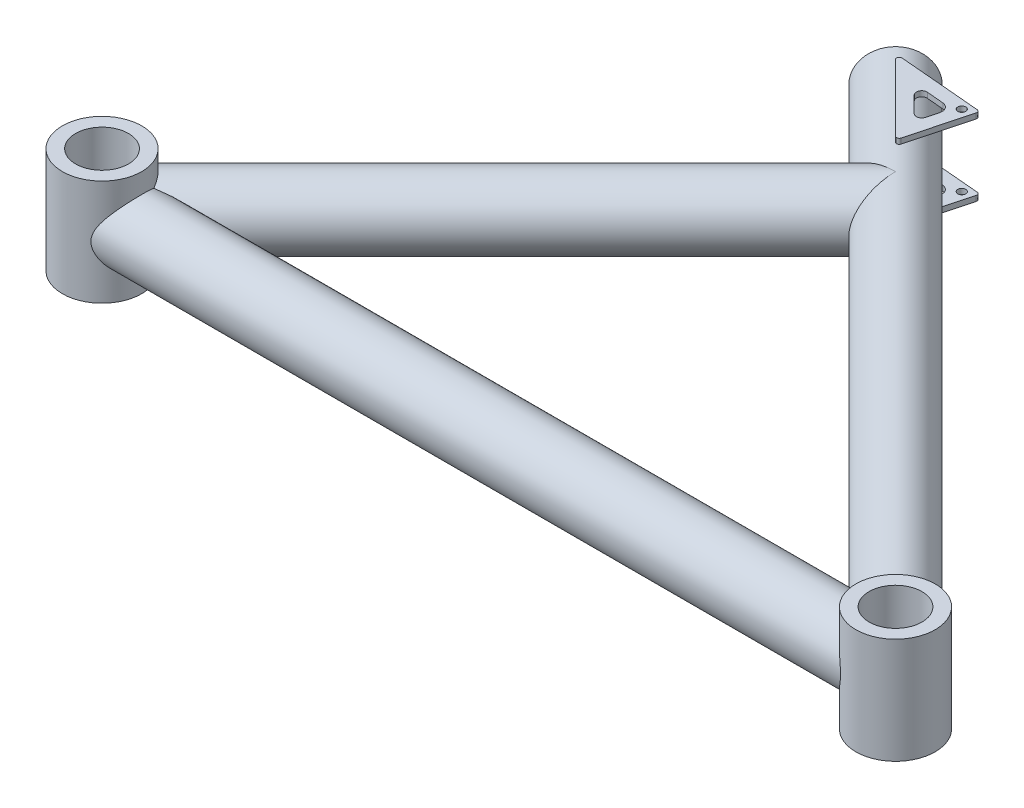
SolidWorks part; units mm, degrees
ref_plane "Alzado" through (0, 0, 0) normal (0, 0, 1) x (1, 0, 0)
ref_plane "Planta" through (0, 0, 0) normal (0, 1, 0) x (1, 0, 0)
ref_plane "Vista lateral" through (0, 0, 0) normal (1, 0, 0) x (0, 0, -1)
sketch "Croquis1" plane through (0, 0, 0) normal (0, 1, 0) x (1, 0, 0)
  circle A0 centre (0, 0) radius 15
  dimension "D1" = 30
extrude "Saliente-Extruir1" add sketch "Croquis1" along normal mid plane 40
sketch "Croquis2" plane through (0, 0, 0) normal (0, 1, 0) x (1, 0, 0)
  line L0 (0, 15) -> (0, -15) construction
  line L1 (-15, 0) -> (15, 0) construction
  line L2 (-10.6066, 10.6066) -> (10.6066, -10.6066) construction
  line L3 (-2.7135, -2.7135) -> (2.0786, 2.0786) construction
  circle A0 centre (0, 0) radius 15 construction
  dimension "D1" = 45
sketch "Croquis9" plane through (0, 0, 0) normal (0, 1, 0) x (1, 0, 0)
  circle A0 centre (300, 0) radius 15
  point P2 (0, 0)
  dimension "D1" = 30
  dimension "D2" = 300
extrude "Saliente-Extruir5" add sketch "Croquis9" along normal mid plane 40 separate body
sketch "Croquis10" plane through (0, 0, 0) normal (0, 0, 1) x (1, 0, 0)
  line L0 (285, 20) -> (285, -20) construction
  line L1 (285, -20) -> (315, -20) construction
  line L2 (285, -20) -> (315, -20) construction
  line L3 (315, -20) -> (315, 20) construction
  line L4 (315, -20) -> (315, 20) construction
  line L5 (315, 20) -> (285, 20) construction
  line L6 (300, 20) -> (300, -20) construction
  line L7 (0, 0) -> (300, 0)
  line L8 (300, 0) -> (300, 12.5)
  line L9 (300, 12.5) -> (0, 12.5)
  line L10 (0, 12.5) -> (0, 0)
  dimension "D1" = 12.5
revolve "Revolución1" add sketch "Croquis10" angle 360 about L7
sketch "Croquis11" plane through (0, 0, 0) normal (0, 1, 0) x (1, 0, 0)
  line L0 (300, 15) -> (300, -15) construction
  line L1 (285, 0) -> (315, 0) construction
  line L2 (271.2614, -28.7386) -> (321.402, 21.402) construction
  line L3 (302.3084, -2.3084) -> (296.4902, 3.5098) construction
  circle A0 centre (300, 0) radius 15 construction
  circle A1 centre (300, 0) radius 15 construction
  point P9 (0, 0)
  dimension "D1" = 45
ref_plane "Plano2" through (150, 0, 150) normal (-0.7071, 0, -0.7071) x (-0.7071, 0, 0.7071)
sketch "Croquis12" plane through (150, 0, 150) normal (-0.7071, 0, -0.7071) x (-0.7071, 0, 0.7071)
  line L0 (-227.132, 0) -> (-197.132, 0) construction
  line L1 (-227.132, 20) -> (-197.132, 20) construction
  line L2 (-227.132, 20) -> (-227.132, -20) construction
  line L3 (-227.132, -20) -> (-197.132, -20) construction
  line L4 (-197.132, 20) -> (-197.132, -20) construction
  line L5 (-212.132, 20) -> (-212.132, -20) construction
  circle A0 centre (-212.132, 0) radius 12.5
  point P10 (-212.132, 0)
  dimension "D1" = 25
extrude "Saliente-Extruir6" add sketch "Croquis12" along normal blind 270
sketch "Croquis17" plane through (0, 0, 0) normal (0, 1, 0) x (1, 0, 0)
  line L0 (0, 15) -> (0, -15) construction
  line L1 (-15, 0) -> (15, 0) construction
  line L2 (-10.6066, 10.6066) -> (10.6066, -10.6066) construction
  line L3 (-8.8388, 8.8388) -> (0, 0)
  line L4 (109.0812, 190.9188) -> (300, 0) construction
  line L5 (117.92, 199.7577) -> (100.2423, 182.08) construction
  line L6 (-8.8388, 8.8388) -> (141.1612, 158.8388)
  line L7 (141.1612, 158.8388) -> (150, 150)
  line L8 (150, 150) -> (0, 0)
  circle A0 centre (0, 0) radius 15 construction
  circle A1 centre (0, 0) radius 15 construction
  point P15 (132.1974, 167.8026)
  dimension "D1" = 45
  dimension "D2" = 12.5
revolve "Revolución2" add sketch "Croquis17" angle 360 about L8
sketch "Croquis18" plane through (0, 20, 0) normal (0, 1, 0) x (1, 0, 0)
  circle A0 centre (0, 0) radius 10
  circle A1 centre (300, 0) radius 10
  circle A2 centre (0, 0) radius 15 construction
  circle A3 centre (300, 0) radius 15 construction
  dimension "D1" = 5
  dimension "D2" = 5
extrude "Cortar-Extruir1" cut sketch "Croquis18" against normal through all contours A1 | A0
ref_plane "Plano3" through (0, 12.5, 0) normal (0, 1, 0) x (1, 0, 0)
sketch "Croquis19" plane through (0, 12.5, 0) normal (0, 1, 0) x (1, 0, 0)
  line L0 (150, 132.3223) -> (269.8223, 12.5) construction
  line L1 (100.2423, 182.08) -> (132.3223, 150) construction
  line L2 (117.92, 199.7577) -> (100.2423, 182.08) construction
  line L3 (302.9758, 14.7019) -> (117.92, 199.7577) construction
  line L4 (150, 132.3223) -> (269.8223, 12.5) construction
  line L5 (100.2423, 182.08) -> (132.3223, 150) construction
  line L6 (117.92, 199.7577) -> (100.2423, 182.08) construction
  line L7 (302.9758, 14.7019) -> (117.92, 199.7577) construction
  line L8 (109.0812, 190.9188) -> (300, 0) construction
  line L9 (113.3238, 186.6762) -> (148.3238, 183.6141)
  line L10 (148.3238, 183.6141) -> (141.6081, 158.3919)
  line L11 (141.6081, 158.3919) -> (113.3238, 186.6762)
  line L12 (132.0472, 180.019) -> (138.4054, 179.4627)
  line L13 (141.043, 175.7023) -> (139.9017, 171.4159)
  line L14 (136.5548, 170.5163) -> (130.4587, 176.6124)
  line L15 (141.9614, 179.1516) -> (139.0087, 168.0623) construction
  line L16 (139.0087, 168.0623) -> (126.5731, 180.4979) construction
  line L17 (126.5731, 180.4979) -> (141.9614, 179.1516) construction
  arc A0 (139.9017, 171.4159) -> (136.5548, 170.5163) centre (137.969, 171.9305) cw
  arc A1 (132.0472, 180.019) -> (130.4587, 176.6124) centre (131.8729, 178.0266) ccw
  arc A2 (138.4054, 179.4627) -> (141.043, 175.7023) centre (138.144, 176.4741) cw
  circle A3 centre (144.0776, 180.9741) radius 1.5
  dimension "D1" = 40
  dimension "D6" = 2
  dimension "D7" = 3
  dimension "D8" = 3
  dimension "D2" = 6
  dimension "D4" = 35
  dimension "D3" = 40
  dimension "D9" = 3
  dimension "D10" = 5
  dimension "D5" = 5
extrude "Saliente-Extruir7" add sketch "Croquis19" along normal blind 2 separate body contours L11 L10 L9 A3 L12 A2 L13 A0 L14 A1
fillet "Redondeo1" radius 1 3 edges at (141.6081, 13.5, -158.3919) (113.3238, 13.5, -186.6762) (148.3238, 13.5, -183.6141)
ref_plane "Plano4" through (0, -12.5, 0) normal (0, -1, 0) x (-1, 0, 0)
sketch "Croquis20" plane through (0, -12.5, 0) normal (0, -1, 0) x (-1, 0, 0)
  line L0 (-141.043, 175.7023) -> (-139.9017, 171.4159) construction
  line L1 (-132.0472, 180.019) -> (-138.4054, 179.4627) construction
  line L2 (-141.043, 175.7023) -> (-139.9017, 171.4159)
  line L3 (-148.0177, 182.4643) -> (-142.0545, 160.0687)
  line L4 (-140.3811, 159.6189) -> (-115.2666, 184.7334)
  line L5 (-116.0608, 186.4367) -> (-147.1385, 183.7178)
  line L6 (-148.0177, 182.4643) -> (-142.0545, 160.0687)
  line L7 (-140.3811, 159.6189) -> (-115.2666, 184.7334)
  line L8 (-116.0608, 186.4367) -> (-147.1385, 183.7178)
  line L9 (-132.0472, 180.019) -> (-138.4054, 179.4627)
  line L13 (-113.3238, 186.6762) -> (-148.3238, 183.6141)
  line L14 (-148.3238, 183.6141) -> (-141.6081, 158.3919)
  line L15 (-141.6081, 158.3919) -> (-113.3238, 186.6762)
  line L16 (-116.0608, 186.4367) -> (-147.1385, 183.7178)
  line L17 (-148.0177, 182.4643) -> (-142.0545, 160.0687)
  line L18 (-140.3811, 159.6189) -> (-115.2666, 184.7334)
  line L19 (-132.0472, 180.019) -> (-138.4054, 179.4627)
  line L20 (-141.043, 175.7023) -> (-139.9017, 171.4159)
  line L21 (-136.5548, 170.5163) -> (-130.4587, 176.6124)
  line L22 (-132.0472, 180.019) -> (-138.4054, 179.4627)
  line L23 (-141.043, 175.7023) -> (-139.9017, 171.4159)
  line L24 (-136.5548, 170.5163) -> (-130.4587, 176.6124)
  circle A0 centre (-144.0776, 180.9741) radius 1.5 construction
  arc A1 (-138.4054, 179.4627) -> (-141.043, 175.7023) centre (-138.144, 176.4741) ccw construction
  circle A2 centre (-144.0776, 180.9741) radius 1.5
  arc A3 (-142.0545, 160.0687) -> (-140.3811, 159.6189) centre (-141.0882, 160.326) ccw
  arc A4 (-115.2666, 184.7334) -> (-116.0608, 186.4367) centre (-115.9737, 185.4405) ccw
  arc A5 (-147.1385, 183.7178) -> (-148.0177, 182.4643) centre (-147.0513, 182.7216) ccw
  arc A6 (-142.0545, 160.0687) -> (-140.3811, 159.6189) centre (-141.0882, 160.326) ccw
  arc A7 (-115.2666, 184.7334) -> (-116.0608, 186.4367) centre (-115.9737, 185.4405) ccw
  arc A8 (-147.1385, 183.7178) -> (-148.0177, 182.4643) centre (-147.0513, 182.7216) ccw
  arc A9 (-138.4054, 179.4627) -> (-141.043, 175.7023) centre (-138.144, 176.4741) ccw
  circle A11 centre (-144.0776, 180.9741) radius 1.5
  circle A12 centre (-144.0776, 180.9741) radius 1.5
  arc A15 (-138.4054, 179.4627) -> (-141.043, 175.7023) centre (-138.144, 176.4741) ccw
  arc A16 (-139.9017, 171.4159) -> (-136.5548, 170.5163) centre (-137.969, 171.9305) ccw
  arc A17 (-130.4587, 176.6124) -> (-132.0472, 180.019) centre (-131.8729, 178.0266) ccw
  arc A18 (-138.4054, 179.4627) -> (-141.043, 175.7023) centre (-138.144, 176.4741) ccw
  arc A19 (-139.9017, 171.4159) -> (-136.5548, 170.5163) centre (-137.969, 171.9305) ccw
  arc A20 (-130.4587, 176.6124) -> (-132.0472, 180.019) centre (-131.8729, 178.0266) ccw
  dimension "D1" = 0
  dimension "D2" = 0
  dimension "D3" = 0
  dimension "D4" = 0
extrude "Saliente-Extruir8" add sketch "Croquis20" along normal blind 2 separate body contours L8 A8 L6 A6 L7 A7 A20 L24 A19 L2 A9 L9 A2
sketch "Croquis21" plane through (-40.9188, 0, -40.9188) normal (-0.7071, 0, -0.7071) x (-0.7071, 0, 0.7071)
  circle A0 centre (-212.132, 0) radius 7.5
  circle A1 centre (-212.132, 0) radius 12.5 construction
  dimension "D1" = 5
extrude "Cortar-Extruir2" cut sketch "Croquis21" against normal blind 250
equation "\"Diam1\"= 30"
equation "\"Large1\"= 40"
equation "\"Ang1\" = 45"
equation "\"Large2\"= 212.5"
equation "\"Diam2\"= 25"
equation "\"D1@Croquis1\"=\"Diam1\""
equation "\"D1@Saliente-Extruir1\"=\"Large1\""
equation "\"Large3\"= 300"
equation "\"D1@Croquis9\"=\"Diam1\""
equation "\"D2@Croquis9\"=\"Large3\""
equation "\"D1@Saliente-Extruir5\"=\"Large1\""
equation "\"D1@Croquis10\"=\"Diam2\"/2"
equation "\"D1@Croquis12\"=\"Diam2\""
equation "\"Large4\"=270"
equation "\"D1@Saliente-Extruir6\"=\"Large4\""
equation "\"D1@Croquis17\"=\"Ang1\""
equation "\"D2@Croquis17\"=\"Diam2\"/2"
equation "\"Esp1\"=5"
equation "\"D1@Croquis18\"=\"Esp1\""
equation "\"D2@Croquis18\"=\"Esp1\""
equation "\"Large5\"=40"
equation "\"D1@Croquis19\"=\"Large5\""
equation "\"Dist\"=6"
equation "\"D2@Croquis19\"=\"Dist\""
equation "\"Lado1\" =35"
equation "\"D4@Croquis19\"=\"Lado1\""
equation "\"AngTr\"=40"
equation "\"D3@Croquis19\"=\"AngTr\""
equation "\"DiamSpring\"=3"
equation "\"D8@Croquis19\"=\"DiamSpring\""
equation "\"Dist1Tr\" = 5"
equation "\"D10@Croquis19\"=\"Dist1Tr\""
equation "\"Dist2Tr\"= 3"
equation "\"D9@Croquis19\"=\"Dist2Tr\""
equation "\"GrosTr\"=2"
equation "\"D1@Saliente-Extruir7\"=\"GrosTr\""
equation "\"D1@Saliente-Extruir8\"=\"GrosTr\""
equation "\"EspTr\" = 5"
equation "\"D5@Croquis19\"=\"EspTr\""
equation "\"Esp2\"=5"
equation "\"D1@Croquis21\"=\"Esp2\""
equation "\"Cort1\"=250"
equation "\"D1@Cortar-Extruir2\"=\"Cort1\""
